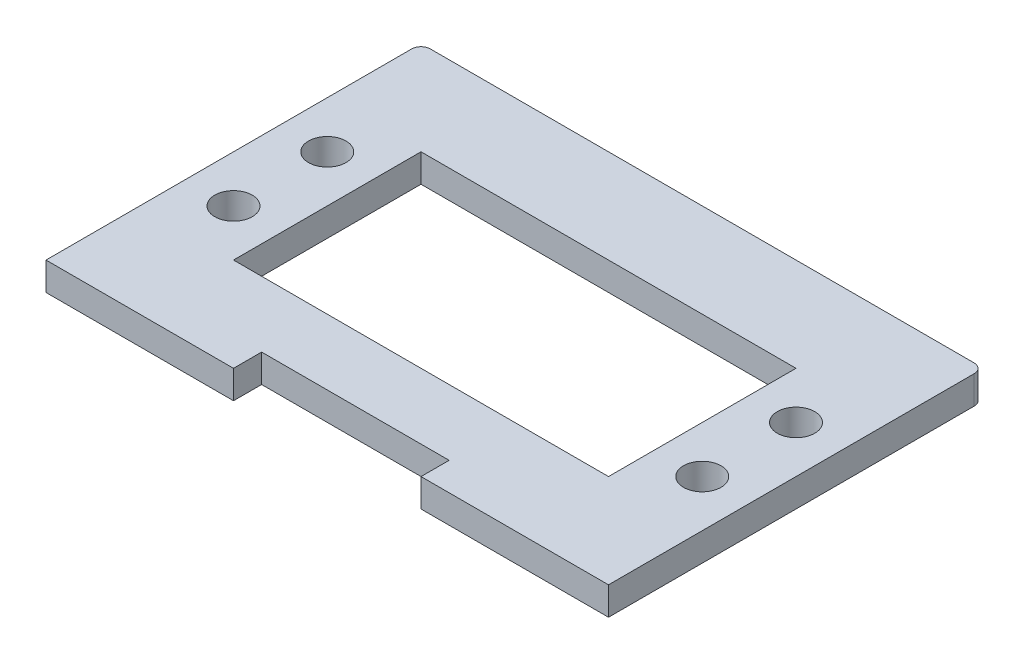
SolidWorks part; units mm, degrees
material "Acrylic (Medium-high impact)"
ref_plane "Front Plane" through (0, 0, 0) normal (0, 0, 1) x (1, 0, 0)
ref_plane "Top Plane" through (0, 0, 0) normal (0, 1, 0) x (1, 0, 0)
ref_plane "Right Plane" through (0, 0, 0) normal (1, 0, 0) x (0, 0, -1)
sketch "Sketch1" plane through (0, 0, 0) normal (0, 1, 0) x (1, 0, 0)
  line L1 (30, -20) -> (-30, -20)
  line L2 (30, -20) -> (30, 20)
  line L3 (30, 20) -> (-30, 20)
  line L4 (-30, -20) -> (-30, 20)
  line L5 (30, -20) -> (-30, 20) construction
  line L6 (30, 20) -> (-30, -20) construction
  point P0 (0, 0)
  dimension "D1" = 60
  dimension "D2" = 40
extrude "Boss-Extrude1" add sketch "Sketch1" along normal blind 3
sketch "Sketch2" plane through (0, 3, 0) normal (0, 1, 0) x (1, 0, 0)
  line L1 (20, -10) -> (-20, -10)
  line L2 (20, -10) -> (20, 10)
  line L3 (20, 10) -> (-20, 10)
  line L4 (-20, -10) -> (-20, 10)
  line L5 (20, -10) -> (-20, 10) construction
  line L6 (20, 10) -> (-20, -10) construction
  point P0 (0, 0)
  dimension "D1" = 40
  dimension "D2" = 20
extrude "Cut-Extrude1" cut sketch "Sketch2" against normal blind 3
sketch "Sketch3" plane through (0, 3, 0) normal (0, 1, 0) x (1, 0, 0)
  line L0 (20, -10) -> (20, 10) construction
  line L1 (20, 10) -> (-20, 10) construction
  line L2 (30, 0) -> (-30, 0) construction
  line L3 (30, -20) -> (30, 20) construction
  line L4 (-30, 20) -> (-30, -20) construction
  line L5 (0, 20) -> (0, -20) construction
  line L6 (30, 20) -> (-30, 20) construction
  line L7 (-30, -20) -> (30, -20) construction
  circle A0 centre (25, 5) radius 2
  circle A1 centre (25, -5) radius 2
  circle A2 centre (-25, -5) radius 2
  circle A3 centre (-25, 5) radius 2
  dimension "D1" = 4
  dimension "D2" = 5
  dimension "D3" = 5
extrude "Cut-Extrude2" cut sketch "Sketch3" against normal blind 3
fillet "Fillet2" radius 1 2 edges at (-30, 1.5, -20) (30, 1.5, -20)
sketch "Sketch4" plane through (0, 3, 0) normal (0, 1, 0) x (1, 0, 0)
  line L0 (-30, -20) -> (30, -20) construction
  line L1 (10, -23) -> (-10, -23)
  line L2 (10, -23) -> (10, -17)
  line L3 (10, -17) -> (-10, -17)
  line L4 (-10, -23) -> (-10, -17)
  line L5 (10, -23) -> (-10, -17) construction
  line L6 (10, -17) -> (-10, -23) construction
  line L7 (-30, 19) -> (-30, -20) construction
  point P0 (0, -20)
  dimension "D1" = 6
  dimension "D2" = 20
extrude "Cut-Extrude3" cut sketch "Sketch4" against normal blind 3
